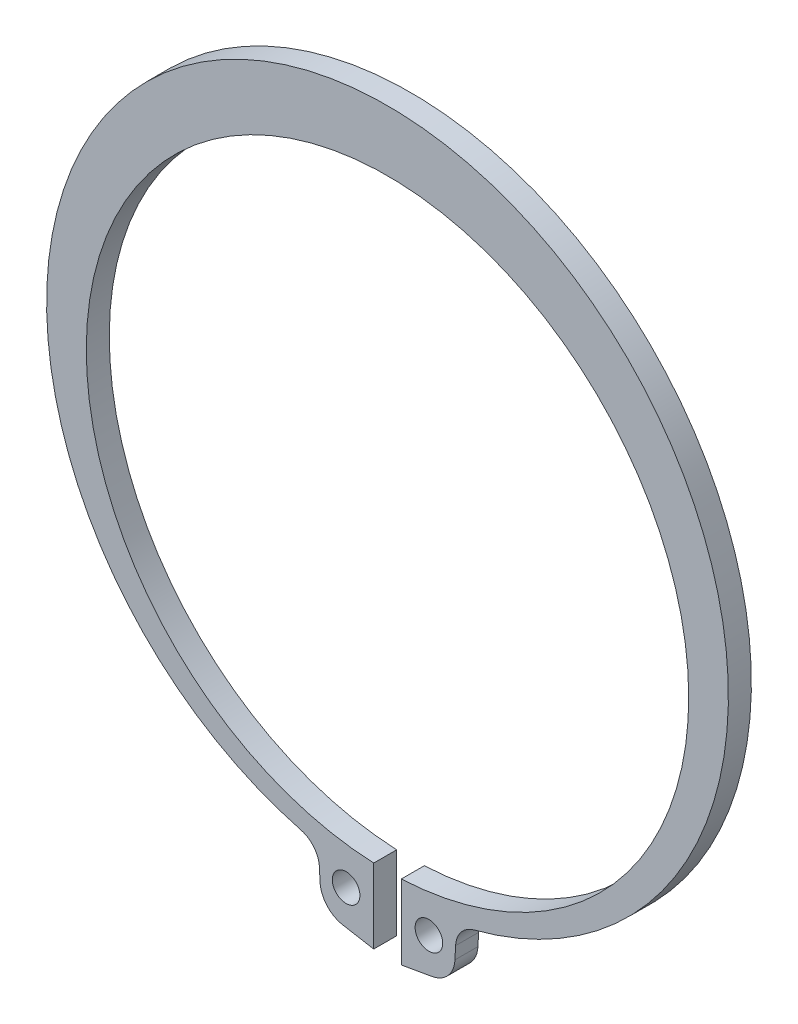
SolidWorks part; units mm, degrees
ref_plane "前视基准面" through (0, 0, 0) normal (0, 0, 1) x (1, 0, 0)
ref_plane "上视基准面" through (0, 0, 0) normal (0, 1, 0) x (1, 0, 0)
ref_plane "右视基准面" through (0, 0, 0) normal (1, 0, 0) x (0, 0, -1)
sketch "草图1" plane through (0, 0, 0) normal (0, 0, 1) x (1, 0, 0)
  line L0 (-43.5, 0) -> (43.5, 0) construction
  line L1 (0, 43.5) -> (0, -43.5) construction
  line L2 (1.5, -32.7156) -> (1.5, -40.8156)
  line L3 (1.5, -40.8156) -> (4.8588, -40.2234)
  line L4 (7.3343, -37.4148) -> (7.5, -34.0082)
  circle A0 centre (0, 0) radius 43.5 construction
  circle A1 centre (0, 0) radius 32.75
  circle A2 centre (4.5, -36.5238) radius 1.5
  circle A3 centre (0, 2.2875) radius 37.0625
  circle A4 centre (0, 0) radius 36.8 construction
  circle A5 centre (0, -0.7468) radius 40.0968 construction
  circle A7 centre (0, 0) radius 33.5 construction
  circle A8 centre (0, 0) radius 35 construction
  arc A9 (7.3343, -37.4148) -> (4.8588, -40.2234) centre (4.3378, -37.269) cw
  point P8 (0, 39.35)
  point P9 (0, 32.75)
  point P25 (0, -32.75)
  point P26 (0, -34.775)
  dimension "D1" = 3
  dimension "d4" = 87
  dimension "d3" = 65.5
  dimension "d5" = 3
  dimension "D6" = 3
  dimension "D8" = 2.025
  dimension "d2" = 67
  dimension "(d1)" = 70
  dimension "D9" = 73.6
  dimension "b" = 6.6
  dimension "a" = 8.1
  dimension "D43" = 9
  dimension "D10" = 80
  dimension "D11" = 6
sketch "草图2" plane through (0, 0, 0) normal (0, 0, 1) x (1, 0, 0)
  line L0 (7.3343, -37.4148) -> (7.5, -34.0082) construction
  line L1 (1.5, -40.8156) -> (4.8588, -40.2234) construction
  line L2 (1.5, -32.7156) -> (1.5, -40.8156) construction
  line L3 (0, 43.5) -> (0, -43.5) construction
  line L4 (7.3343, -37.4148) -> (7.5, -34.0082)
  line L5 (1.5, -40.8156) -> (4.8588, -40.2234)
  line L6 (1.5, -32.7156) -> (1.5, -40.8156)
  line L7 (0, 43.5) -> (0, -43.5) construction
  line L8 (-1.5, -40.8156) -> (-4.8588, -40.2234)
  line L9 (-7.3343, -37.4148) -> (-7.5, -34.0082)
  line L10 (-1.5, -32.7156) -> (-1.5, -40.8156)
  circle A0 centre (0, 0) radius 32.75 construction
  circle A1 centre (0, 2.2875) radius 37.0625 construction
  arc A3 (1.5, -32.7156) -> (-1.5, -32.7156) centre (0, 0) ccw
  arc A4 (7.5, -34.0082) -> (-7.5, -34.0082) centre (0, 2.2875) ccw
  arc A5 (4.8588, -40.2234) -> (7.3343, -37.4148) centre (4.3378, -37.269) ccw construction
  circle A6 centre (4.5, -36.5238) radius 1.5 construction
  circle A7 centre (4.5, -36.5238) radius 1.5
  circle A8 centre (-4.5, -36.5238) radius 1.5
  arc A9 (-4.8588, -40.2234) -> (-7.3343, -37.4148) centre (-4.3378, -37.269) cw
  arc A10 (4.8588, -40.2234) -> (7.3343, -37.4148) centre (4.3378, -37.269) ccw
extrude "凸台-拉伸1" add sketch "草图2" along normal mid plane 2.5
fillet "圆角1" radius 2.7 2 edges at (7.5, -34.0082, 0) (-7.5, -34.0082, 0)
